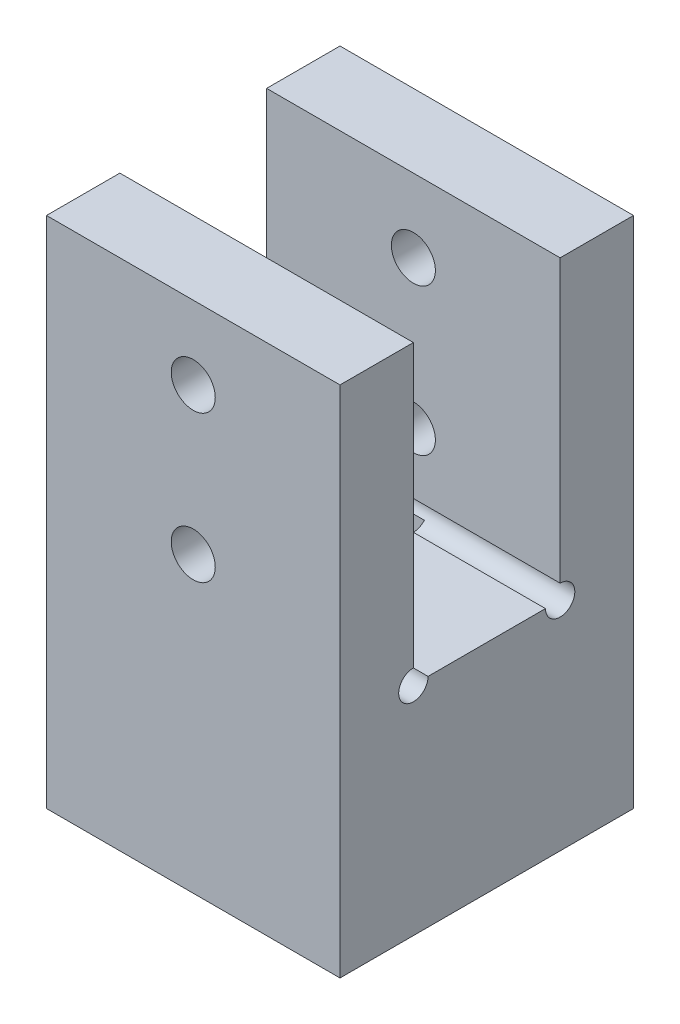
SolidWorks part; units mm, degrees
ref_plane "正面" through (0, 0, 0) normal (0, 0, 1) x (1, 0, 0)
ref_plane "平面" through (0, 0, 0) normal (0, 1, 0) x (1, 0, 0)
ref_plane "右側面" through (0, 0, 0) normal (1, 0, 0) x (0, 0, -1)
sketch "ｽｹｯﾁ1" plane through (0, 0, 0) normal (0, 0, 1) x (1, 0, 0)
  line L1 (-10, -17.5) -> (10, -17.5)
  line L2 (-10, -17.5) -> (-10, 17.5)
  line L3 (-10, 17.5) -> (10, 17.5)
  line L4 (10, -17.5) -> (10, 17.5)
  line L5 (-10, -17.5) -> (10, 17.5) construction
  line L6 (-10, 17.5) -> (10, -17.5) construction
  point P0 (0, 0)
  dimension "D1" = 35
  dimension "D2" = 20
extrude "ﾎﾞｽ - 押し出し1" add sketch "ｽｹｯﾁ1" along normal blind 5
sketch "ｽｹｯﾁ2" plane through (0, 0, 5) normal (0, 0, 1) x (1, 0, 0)
  line L0 (0, 17.5) -> (0, -17.5) construction
  line L1 (10, 17.5) -> (-10, 17.5) construction
  line L2 (-10, -17.5) -> (10, -17.5) construction
  line L3 (0, -2.7) -> (0, -17.5)
  line L4 (-10, -2.7) -> (10, -2.7) construction
  line L5 (-10, -2.7) -> (-10, 17.5) construction
  line L6 (-10, 17.5) -> (10, 17.5) construction
  line L7 (10, -2.7) -> (10, 17.5) construction
  line L8 (-10, -2.7) -> (10, 17.5) construction
  line L9 (-10, 17.5) -> (10, -2.7) construction
  line L10 (0, -17.5) -> (10, -17.5)
  line L11 (10, -17.5) -> (10, -2.7)
  line L12 (10, -2.7) -> (0, -2.7)
  point P6 (0, 7.4)
  dimension "D1" = 20.2
  dimension "D2" = 10
extrude "ﾎﾞｽ - 押し出し2" add sketch "ｽｹｯﾁ2" along normal blind 10
sketch "ｽｹｯﾁ3" plane through (0, 0, 15) normal (0, 0, 1) x (1, 0, 0)
  line L0 (-10, 17.5) -> (-10, -17.5) construction
  line L1 (10, -17.5) -> (-10, -17.5)
  line L2 (10, -17.5) -> (10, 17.5)
  line L3 (10, 17.5) -> (-10, 17.5)
  line L4 (-10, -17.5) -> (-10, 17.5)
  line L5 (10, 17.5) -> (-10, 17.5) construction
extrude "ﾎﾞｽ - 押し出し3" add sketch "ｽｹｯﾁ3" along normal blind 5
sketch "ｽｹｯﾁ4" plane through (10, 0, 0) normal (1, 0, 0) x (0, 0, -1)
  line L0 (-10, -2.7) -> (-10, -17.5) construction
  line L1 (-15, -2.7) -> (-5, -2.7) construction
  line L2 (-20, -17.5) -> (0, -17.5) construction
  circle A0 centre (-15, -2.7) radius 1
  circle A1 centre (-5, -2.7) radius 1
  dimension "D1" = 2
extrude "ｶｯﾄ - 押し出し1" cut sketch "ｽｹｯﾁ4" against normal through all
sketch "ｽｹｯﾁ5" plane through (0, 0, 20) normal (0, 0, 1) x (1, 0, 0)
  line L0 (0, 17.5) -> (0, -17.5) construction
  line L1 (10, 17.5) -> (-10, 17.5) construction
  line L2 (-10, -17.5) -> (10, -17.5) construction
  circle A0 centre (0, 12.5) radius 1.5
  circle A1 centre (0, 2.5) radius 1.5
  dimension "D1" = 5
  dimension "D2" = 10
  dimension "D3" = 3
extrude "ｶｯﾄ - 押し出し2" cut sketch "ｽｹｯﾁ5" against normal through all
sketch "ｽｹｯﾁ6" plane through (0, 0, 0) normal (-1, 0, 0) x (0, 0, 1)
  line L0 (5, -17.5) -> (0, -17.5) construction
  line L1 (4.25, -17.5) -> (15.75, -17.5)
  line L2 (4.25, -17.5) -> (4.25, -2.7)
  line L3 (4.25, -2.7) -> (15.75, -2.7)
  line L4 (15.75, -17.5) -> (15.75, -2.7)
  line L5 (14, -2.7) -> (6, -2.7) construction
  line L6 (10, -17.5) -> (10, -2.7) construction
  line L7 (15, -17.5) -> (5, -17.5) construction
  point P10 (16.1795, -2.7)
  point P11 (10, -17.5)
  dimension "D1" = 11.5
extrude "ｶｯﾄ - 押し出し3" cut sketch "ｽｹｯﾁ6" along normal up to surface (10 mm away) up to face at (-10, -0.9, 16.8333)
